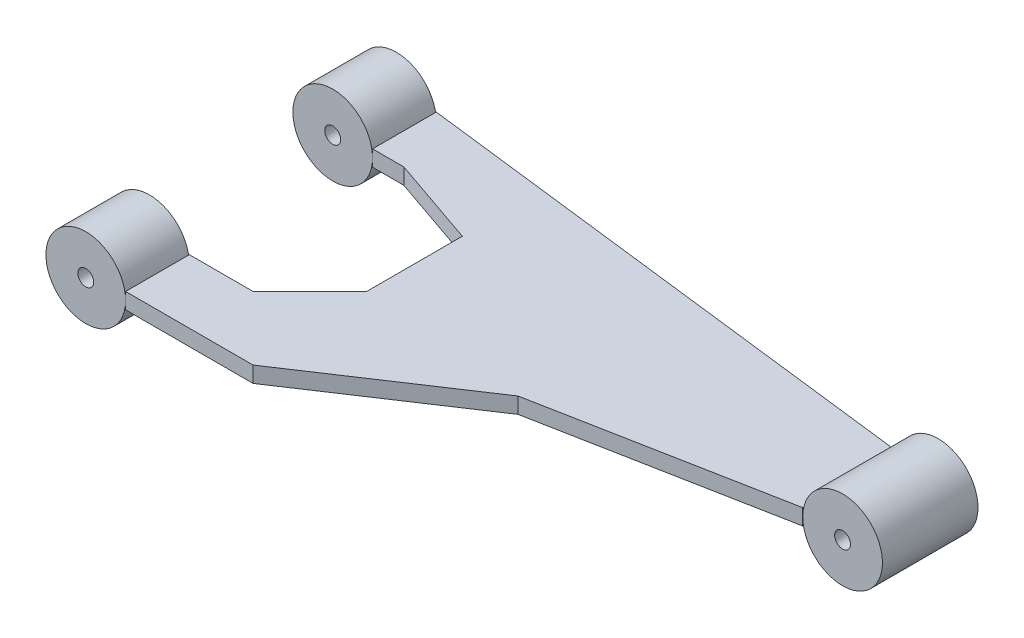
SolidWorks part; units mm, degrees
ref_plane "Front Plane" through (0, 0, 0) normal (0, 0, 1) x (1, 0, 0)
ref_plane "Top Plane" through (0, 0, 0) normal (0, 1, 0) x (1, 0, 0)
ref_plane "Right Plane" through (0, 0, 0) normal (1, 0, 0) x (0, 0, -1)
sketch "Sketch1" plane through (0, 0, 0) normal (0, 0, 1) x (1, 0, 0)
  line L0 (0, 0) -> (241.3, 0) construction
  circle A0 centre (0, 0) radius 15.875
  circle A1 centre (241.3, 0) radius 15.875
  circle A2 centre (0, 0) radius 3.175
  circle A3 centre (241.3, 0) radius 3.175
  dimension "D1" = 31.75
  dimension "D2" = 241.3
  dimension "D3" = 6.35
extrude "Boss-Extrude1" add sketch "Sketch1" along normal blind 123.825
sketch "Sketch2" plane through (0, 0, 0) normal (0, 1, 0) x (1, 0, 0)
  line L0 (15.875, 0) -> (225.425, -25.4)
  line L1 (225.425, -25.4) -> (225.425, -63.5)
  line L2 (15.875, -123.825) -> (66.675, -123.825)
  line L3 (66.675, -123.825) -> (130.175, -81.7039)
  line L4 (130.175, -81.7039) -> (225.425, -63.5)
  line L5 (225.425, 0) -> (225.425, -123.825) construction
  line L6 (257.175, 0) -> (225.425, 0) construction
  line L7 (15.875, -25.4) -> (28.3552, -25.4)
  line L8 (15.875, -123.825) -> (15.875, 0) construction
  line L9 (28.3552, -25.4) -> (63.9217, -37.6783)
  line L10 (63.9217, -37.6783) -> (63.9217, -75.7783)
  line L11 (63.9217, -75.7783) -> (41.275, -98.425)
  line L12 (41.275, -98.425) -> (15.875, -98.425)
  line L13 (15.875, 0) -> (15.875, -25.4)
  line L14 (15.875, -98.425) -> (15.875, -123.825)
  dimension "D1" = 25.4
  dimension "D2" = 38.1
  dimension "D3" = 50.8
  dimension "D4" = 76.2
  dimension "D5" = 63.5
  dimension "D6" = 25.4
  dimension "D7" = 25.4
  dimension "D8" = 38.1
  dimension "D9" = 45
  dimension "D10" = 25.4
extrude "Boss-Extrude2" add sketch "Sketch2" along normal mid plane 6.35 separate body
sketch "Sketch3" plane through (0, 0, 0) normal (0, 1, 0) x (1, 0, 0)
  line L0 (-15.875, 0) -> (-15.875, -123.825) construction
  line L1 (15.875, -25.4) -> (-15.875, -25.4)
  line L2 (15.875, -25.4) -> (15.875, -98.425)
  line L3 (15.875, -98.425) -> (-15.875, -98.425)
  line L4 (-15.875, -25.4) -> (-15.875, -98.425)
  line L5 (225.425, -25.4) -> (257.175, -25.4)
  line L6 (225.425, -25.4) -> (225.425, 0)
  line L7 (225.425, 0) -> (257.175, 0)
  line L8 (257.175, -25.4) -> (257.175, 0)
  line L9 (225.425, -63.5) -> (257.175, -63.5)
  line L10 (225.425, -63.5) -> (225.425, -123.825)
  line L11 (225.425, -123.825) -> (257.175, -123.825)
  line L12 (257.175, -63.5) -> (257.175, -123.825)
extrude "Cut-Extrude1" cut sketch "Sketch3" against normal through all both and the other way through all
